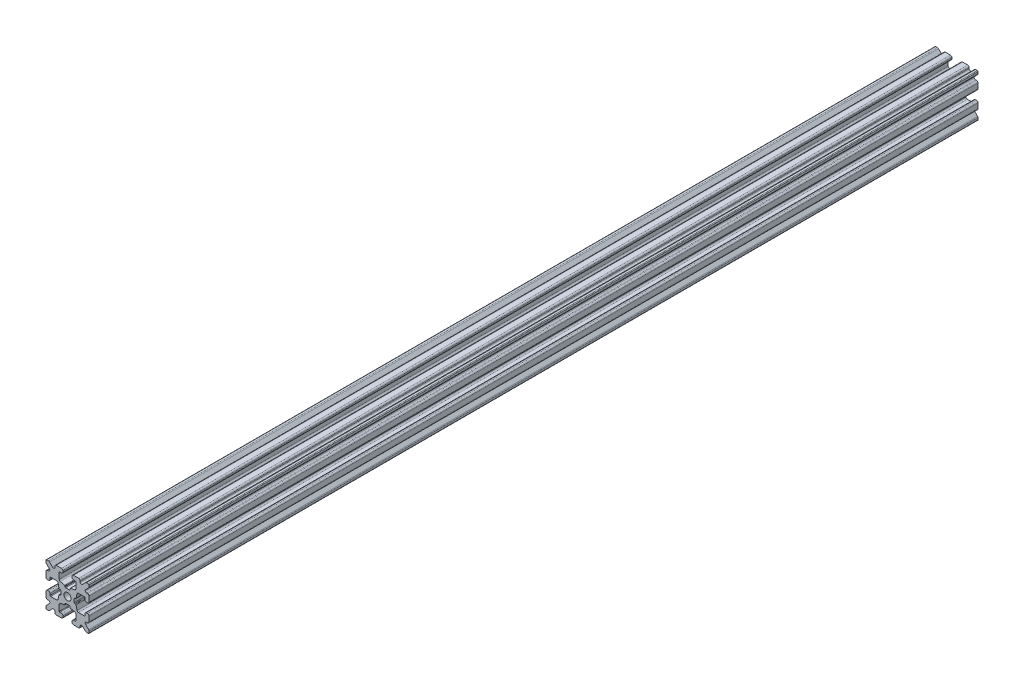
SolidWorks part; units mm, degrees
ref_plane "Alzado" through (0, 0, 0) normal (0, 0, 1) x (1, 0, 0)
ref_plane "Planta" through (0, 0, 0) normal (0, 1, 0) x (1, 0, 0)
ref_plane "Vista lateral" through (0, 0, 0) normal (1, 0, 0) x (0, 0, -1)
ref_plane "Plano1" through (0, 0, -150) normal (0, 0, -1) x (-1, 0, 0)
sketch "Croquis1" plane through (0, 0, -150) normal (0, 0, -1) x (-1, 0, 0)
  line L0 (-2.9, -5.9) -> (-2.9, -3.8003)
  line L1 (-2.5094, -3.3124) -> (-0.9818, -2.97)
  line L2 (-0.8255, -2.7749) -> (-0.8255, -2.5471)
  line L3 (-0.6255, -2.3471) -> (0.6255, -2.3471)
  line L4 (0.8255, -2.5471) -> (0.8255, -2.7749)
  line L5 (0.9818, -2.97) -> (2.5094, -3.3124)
  line L6 (2.9, -3.8003) -> (2.9, -5.9)
  line L7 (2.7, -6.1) -> (2.1, -6.1)
  line L8 (1.6, -6.6) -> (1.6, -7)
  line L9 (2.1, -7.5) -> (3.9, -7.5)
  line L10 (4.4, -7) -> (4.4, -6.6678)
  line L11 (5.2536, -6.3142) -> (6.2929, -7.3536)
  line L12 (6.6464, -7.5) -> (7.25, -7.5)
  line L13 (7.5, -7.25) -> (7.5, -6.6464)
  line L14 (7.3536, -6.2929) -> (6.3142, -5.2536)
  line L15 (6.6678, -4.4) -> (7, -4.4)
  line L16 (7.5, -3.9) -> (7.5, -2.1)
  line L17 (7, -1.6) -> (6.6, -1.6)
  line L18 (6.1, -2.1) -> (6.1, -2.7)
  line L19 (5.9, -2.9) -> (3.8003, -2.9)
  line L20 (3.3124, -2.5094) -> (2.97, -0.9818)
  line L21 (2.7749, -0.8255) -> (2.5471, -0.8255)
  line L22 (2.3471, -0.6255) -> (2.3471, 0.6255)
  line L23 (2.5471, 0.8255) -> (2.7749, 0.8255)
  line L24 (2.97, 0.9818) -> (3.3124, 2.5094)
  line L25 (3.8003, 2.9) -> (5.9, 2.9)
  line L26 (6.1, 2.7) -> (6.1, 2.1)
  line L27 (6.6, 1.6) -> (7, 1.6)
  line L28 (7.5, 2.1) -> (7.5, 3.9)
  line L29 (7, 4.4) -> (6.6678, 4.4)
  line L30 (6.3142, 5.2536) -> (7.3536, 6.2929)
  line L31 (7.5, 6.6464) -> (7.5, 7.25)
  line L32 (7.25, 7.5) -> (6.6464, 7.5)
  line L33 (6.2929, 7.3536) -> (5.2536, 6.3142)
  line L34 (4.4, 6.6678) -> (4.4, 7)
  line L35 (3.9, 7.5) -> (2.1, 7.5)
  line L36 (1.6, 7) -> (1.6, 6.6)
  line L37 (2.1, 6.1) -> (2.7, 6.1)
  line L38 (2.9, 5.9) -> (2.9, 3.8003)
  line L39 (2.5094, 3.3124) -> (0.9818, 2.97)
  line L40 (0.8255, 2.7749) -> (0.8255, 2.5471)
  line L41 (0.6255, 2.3471) -> (-0.6255, 2.3471)
  line L42 (-0.8255, 2.5471) -> (-0.8255, 2.7749)
  line L43 (-0.9818, 2.97) -> (-2.5094, 3.3124)
  line L44 (-2.9, 3.8003) -> (-2.9, 5.9)
  line L45 (-2.7, 6.1) -> (-2.1, 6.1)
  line L46 (-1.6, 6.6) -> (-1.6, 7)
  line L47 (-2.1, 7.5) -> (-3.9, 7.5)
  line L48 (-4.4, 7) -> (-4.4, 6.6678)
  line L49 (-5.2536, 6.3142) -> (-6.2929, 7.3536)
  line L50 (-6.6464, 7.5) -> (-7.25, 7.5)
  line L51 (-7.5, 7.25) -> (-7.5, 6.6464)
  line L52 (-7.3536, 6.2929) -> (-6.3142, 5.2536)
  line L53 (-6.6678, 4.4) -> (-7, 4.4)
  line L54 (-7.5, 3.9) -> (-7.5, 2.1)
  line L55 (-7, 1.6) -> (-6.6, 1.6)
  line L56 (-6.1, 2.1) -> (-6.1, 2.7)
  line L57 (-5.9, 2.9) -> (-3.8003, 2.9)
  line L58 (-3.3124, 2.5094) -> (-2.97, 0.9818)
  line L59 (-2.7749, 0.8255) -> (-2.5471, 0.8255)
  line L60 (-2.3471, 0.6255) -> (-2.3471, -0.6255)
  line L61 (-2.5471, -0.8255) -> (-2.7749, -0.8255)
  line L62 (-2.97, -0.9818) -> (-3.3124, -2.5094)
  line L63 (-3.8003, -2.9) -> (-5.9, -2.9)
  line L64 (-6.1, -2.7) -> (-6.1, -2.1)
  line L65 (-6.6, -1.6) -> (-7, -1.6)
  line L66 (-7.5, -2.1) -> (-7.5, -3.9)
  line L67 (-7, -4.4) -> (-6.6678, -4.4)
  line L68 (-6.3142, -5.2536) -> (-7.3536, -6.2929)
  line L69 (-7.5, -6.6464) -> (-7.5, -7.25)
  line L70 (-7.25, -7.5) -> (-6.6464, -7.5)
  line L71 (-6.2929, -7.3536) -> (-5.2536, -6.3142)
  line L72 (-4.4, -6.6678) -> (-4.4, -7)
  line L73 (-3.9, -7.5) -> (-2.1, -7.5)
  line L74 (-1.6, -7) -> (-1.6, -6.6)
  line L75 (-2.1, -6.1) -> (-2.7, -6.1)
  circle A0 centre (0, 0) radius 1.25
  arc A1 (-2.9, -3.8003) -> (-2.5094, -3.3124) centre (-2.4, -3.8003) cw
  arc A2 (-0.9818, -2.97) -> (-0.8255, -2.7749) centre (-1.0255, -2.7749) ccw
  arc A3 (-0.8255, -2.5471) -> (-0.6255, -2.3471) centre (-0.6255, -2.5471) cw
  arc A4 (0.6255, -2.3471) -> (0.8255, -2.5471) centre (0.6255, -2.5471) cw
  arc A5 (0.8255, -2.7749) -> (0.9818, -2.97) centre (1.0255, -2.7749) ccw
  arc A6 (2.5094, -3.3124) -> (2.9, -3.8003) centre (2.4, -3.8003) cw
  arc A7 (2.9, -5.9) -> (2.7, -6.1) centre (2.7, -5.9) cw
  arc A8 (2.1, -6.1) -> (1.6, -6.6) centre (2.1, -6.6) ccw
  arc A9 (1.6, -7) -> (2.1, -7.5) centre (2.1, -7) ccw
  arc A10 (3.9, -7.5) -> (4.4, -7) centre (3.9, -7) ccw
  arc A11 (4.4, -6.6678) -> (5.2536, -6.3142) centre (4.9, -6.6678) cw
  arc A12 (6.2929, -7.3536) -> (6.6464, -7.5) centre (6.6464, -7) ccw
  arc A13 (7.25, -7.5) -> (7.5, -7.25) centre (7.25, -7.25) ccw
  arc A14 (7.5, -6.6464) -> (7.3536, -6.2929) centre (7, -6.6464) ccw
  arc A15 (6.3142, -5.2536) -> (6.6678, -4.4) centre (6.6678, -4.9) cw
  arc A16 (7, -4.4) -> (7.5, -3.9) centre (7, -3.9) ccw
  arc A17 (7.5, -2.1) -> (7, -1.6) centre (7, -2.1) ccw
  arc A18 (6.6, -1.6) -> (6.1, -2.1) centre (6.6, -2.1) ccw
  arc A19 (6.1, -2.7) -> (5.9, -2.9) centre (5.9, -2.7) cw
  arc A20 (3.8003, -2.9) -> (3.3124, -2.5094) centre (3.8003, -2.4) cw
  arc A21 (2.97, -0.9818) -> (2.7749, -0.8255) centre (2.7749, -1.0255) ccw
  arc A22 (2.5471, -0.8255) -> (2.3471, -0.6255) centre (2.5471, -0.6255) cw
  arc A23 (2.3471, 0.6255) -> (2.5471, 0.8255) centre (2.5471, 0.6255) cw
  arc A24 (2.7749, 0.8255) -> (2.97, 0.9818) centre (2.7749, 1.0255) ccw
  arc A25 (3.3124, 2.5094) -> (3.8003, 2.9) centre (3.8003, 2.4) cw
  arc A26 (5.9, 2.9) -> (6.1, 2.7) centre (5.9, 2.7) cw
  arc A27 (6.1, 2.1) -> (6.6, 1.6) centre (6.6, 2.1) ccw
  arc A28 (7, 1.6) -> (7.5, 2.1) centre (7, 2.1) ccw
  arc A29 (7.5, 3.9) -> (7, 4.4) centre (7, 3.9) ccw
  arc A30 (6.6678, 4.4) -> (6.3142, 5.2536) centre (6.6678, 4.9) cw
  arc A31 (7.3536, 6.2929) -> (7.5, 6.6464) centre (7, 6.6464) ccw
  arc A32 (7.5, 7.25) -> (7.25, 7.5) centre (7.25, 7.25) ccw
  arc A33 (6.6464, 7.5) -> (6.2929, 7.3536) centre (6.6464, 7) ccw
  arc A34 (5.2536, 6.3142) -> (4.4, 6.6678) centre (4.9, 6.6678) cw
  arc A35 (4.4, 7) -> (3.9, 7.5) centre (3.9, 7) ccw
  arc A36 (2.1, 7.5) -> (1.6, 7) centre (2.1, 7) ccw
  arc A37 (1.6, 6.6) -> (2.1, 6.1) centre (2.1, 6.6) ccw
  arc A38 (2.7, 6.1) -> (2.9, 5.9) centre (2.7, 5.9) cw
  arc A39 (2.9, 3.8003) -> (2.5094, 3.3124) centre (2.4, 3.8003) cw
  arc A40 (0.9818, 2.97) -> (0.8255, 2.7749) centre (1.0255, 2.7749) ccw
  arc A41 (0.8255, 2.5471) -> (0.6255, 2.3471) centre (0.6255, 2.5471) cw
  arc A42 (-0.6255, 2.3471) -> (-0.8255, 2.5471) centre (-0.6255, 2.5471) cw
  arc A43 (-0.8255, 2.7749) -> (-0.9818, 2.97) centre (-1.0255, 2.7749) ccw
  arc A44 (-2.5094, 3.3124) -> (-2.9, 3.8003) centre (-2.4, 3.8003) cw
  arc A45 (-2.9, 5.9) -> (-2.7, 6.1) centre (-2.7, 5.9) cw
  arc A46 (-2.1, 6.1) -> (-1.6, 6.6) centre (-2.1, 6.6) ccw
  arc A47 (-1.6, 7) -> (-2.1, 7.5) centre (-2.1, 7) ccw
  arc A48 (-3.9, 7.5) -> (-4.4, 7) centre (-3.9, 7) ccw
  arc A49 (-4.4, 6.6678) -> (-5.2536, 6.3142) centre (-4.9, 6.6678) cw
  arc A50 (-6.2929, 7.3536) -> (-6.6464, 7.5) centre (-6.6464, 7) ccw
  arc A51 (-7.25, 7.5) -> (-7.5, 7.25) centre (-7.25, 7.25) ccw
  arc A52 (-7.5, 6.6464) -> (-7.3536, 6.2929) centre (-7, 6.6464) ccw
  arc A53 (-6.3142, 5.2536) -> (-6.6678, 4.4) centre (-6.6678, 4.9) cw
  arc A54 (-7, 4.4) -> (-7.5, 3.9) centre (-7, 3.9) ccw
  arc A55 (-7.5, 2.1) -> (-7, 1.6) centre (-7, 2.1) ccw
  arc A56 (-6.6, 1.6) -> (-6.1, 2.1) centre (-6.6, 2.1) ccw
  arc A57 (-6.1, 2.7) -> (-5.9, 2.9) centre (-5.9, 2.7) cw
  arc A58 (-3.8003, 2.9) -> (-3.3124, 2.5094) centre (-3.8003, 2.4) cw
  arc A59 (-2.97, 0.9818) -> (-2.7749, 0.8255) centre (-2.7749, 1.0255) ccw
  arc A60 (-2.5471, 0.8255) -> (-2.3471, 0.6255) centre (-2.5471, 0.6255) cw
  arc A61 (-2.3471, -0.6255) -> (-2.5471, -0.8255) centre (-2.5471, -0.6255) cw
  arc A62 (-2.7749, -0.8255) -> (-2.97, -0.9818) centre (-2.7749, -1.0255) ccw
  arc A63 (-3.3124, -2.5094) -> (-3.8003, -2.9) centre (-3.8003, -2.4) cw
  arc A64 (-5.9, -2.9) -> (-6.1, -2.7) centre (-5.9, -2.7) cw
  arc A65 (-6.1, -2.1) -> (-6.6, -1.6) centre (-6.6, -2.1) ccw
  arc A66 (-7, -1.6) -> (-7.5, -2.1) centre (-7, -2.1) ccw
  arc A67 (-7.5, -3.9) -> (-7, -4.4) centre (-7, -3.9) ccw
  arc A68 (-6.6678, -4.4) -> (-6.3142, -5.2536) centre (-6.6678, -4.9) cw
  arc A69 (-7.3536, -6.2929) -> (-7.5, -6.6464) centre (-7, -6.6464) ccw
  arc A70 (-7.5, -7.25) -> (-7.25, -7.5) centre (-7.25, -7.25) ccw
  arc A71 (-6.6464, -7.5) -> (-6.2929, -7.3536) centre (-6.6464, -7) ccw
  arc A72 (-5.2536, -6.3142) -> (-4.4, -6.6678) centre (-4.9, -6.6678) cw
  arc A73 (-4.4, -7) -> (-3.9, -7.5) centre (-3.9, -7) ccw
  arc A74 (-2.1, -7.5) -> (-1.6, -7) centre (-2.1, -7) ccw
  arc A75 (-1.6, -6.6) -> (-2.1, -6.1) centre (-2.1, -6.6) ccw
  arc A76 (-2.7, -6.1) -> (-2.9, -5.9) centre (-2.7, -5.9) cw
extrude "Saliente-Extruir1" add sketch "Croquis1" against normal blind 300
sketch "Croquis2" plane through (0, 0, 150) normal (0, 0, 1) x (1, 0, 0)
  line L76 (2.7, -6.1) -> (2.1, -6.1)
  line L77 (1.6, -6.6) -> (1.6, -7)
  line L78 (2.1, -7.5) -> (3.9, -7.5)
  line L79 (4.4, -7) -> (4.4, -6.6678)
  line L80 (5.2536, -6.3142) -> (6.2929, -7.3536)
  line L81 (6.6464, -7.5) -> (7.25, -7.5)
  line L82 (7.5, -7.25) -> (7.5, -6.6464)
  line L83 (7.3536, -6.2929) -> (6.3142, -5.2536)
  line L84 (6.6678, -4.4) -> (7, -4.4)
  line L85 (7.5, -3.9) -> (7.5, -2.1)
  line L86 (7, -1.6) -> (6.6, -1.6)
  line L87 (6.1, -2.1) -> (6.1, -2.7)
  line L88 (5.9, -2.9) -> (3.8003, -2.9)
  line L89 (3.3124, -2.5094) -> (2.97, -0.9818)
  line L90 (2.7749, -0.8255) -> (2.5471, -0.8255)
  line L91 (2.3471, -0.6255) -> (2.3471, 0.6255)
  line L92 (2.5471, 0.8255) -> (2.7749, 0.8255)
  line L93 (2.97, 0.9818) -> (3.3124, 2.5094)
  line L94 (3.8003, 2.9) -> (5.9, 2.9)
  line L95 (6.1, 2.7) -> (6.1, 2.1)
  line L96 (6.6, 1.6) -> (7, 1.6)
  line L97 (7.5, 2.1) -> (7.5, 3.9)
  line L98 (7, 4.4) -> (6.6678, 4.4)
  line L99 (6.3142, 5.2536) -> (7.3536, 6.2929)
  line L100 (7.5, 6.6464) -> (7.5, 7.25)
  line L101 (7.25, 7.5) -> (6.6464, 7.5)
  line L102 (6.2929, 7.3536) -> (5.2536, 6.3142)
  line L103 (4.4, 6.6678) -> (4.4, 7)
  line L104 (3.9, 7.5) -> (2.1, 7.5)
  line L105 (1.6, 7) -> (1.6, 6.6)
  line L106 (2.1, 6.1) -> (2.7, 6.1)
  line L107 (2.9, 5.9) -> (2.9, 3.8003)
  line L108 (2.5094, 3.3124) -> (0.9818, 2.97)
  line L109 (0.8255, 2.7749) -> (0.8255, 2.5471)
  line L110 (0.6255, 2.3471) -> (-0.6255, 2.3471)
  line L111 (-0.8255, 2.5471) -> (-0.8255, 2.7749)
  line L112 (-0.9818, 2.97) -> (-2.5094, 3.3124)
  line L113 (-2.9, 3.8003) -> (-2.9, 5.9)
  line L114 (-2.7, 6.1) -> (-2.1, 6.1)
  line L115 (-1.6, 6.6) -> (-1.6, 7)
  line L116 (-2.1, 7.5) -> (-3.9, 7.5)
  line L117 (-4.4, 7) -> (-4.4, 6.6678)
  line L118 (-5.2536, 6.3142) -> (-6.2929, 7.3536)
  line L119 (-6.6464, 7.5) -> (-7.25, 7.5)
  line L120 (-7.5, 7.25) -> (-7.5, 6.6464)
  line L121 (-7.3536, 6.2929) -> (-6.3142, 5.2536)
  line L122 (-6.6678, 4.4) -> (-7, 4.4)
  line L123 (-7.5, 3.9) -> (-7.5, 2.1)
  line L124 (-7, 1.6) -> (-6.6, 1.6)
  line L125 (-6.1, 2.1) -> (-6.1, 2.7)
  line L126 (-5.9, 2.9) -> (-3.8003, 2.9)
  line L127 (-3.3124, 2.5094) -> (-2.97, 0.9818)
  line L128 (-2.7749, 0.8255) -> (-2.5471, 0.8255)
  line L129 (-2.3471, 0.6255) -> (-2.3471, -0.6255)
  line L130 (-2.5471, -0.8255) -> (-2.7749, -0.8255)
  line L131 (-2.97, -0.9818) -> (-3.3124, -2.5094)
  line L132 (-3.8003, -2.9) -> (-5.9, -2.9)
  line L133 (-6.1, -2.7) -> (-6.1, -2.1)
  line L134 (-6.6, -1.6) -> (-7, -1.6)
  line L135 (-7.5, -2.1) -> (-7.5, -3.9)
  line L136 (-7, -4.4) -> (-6.6678, -4.4)
  line L137 (-6.3142, -5.2536) -> (-7.3536, -6.2929)
  line L138 (-7.5, -6.6464) -> (-7.5, -7.25)
  line L139 (-7.25, -7.5) -> (-6.6464, -7.5)
  line L140 (-6.2929, -7.3536) -> (-5.2536, -6.3142)
  line L141 (-4.4, -6.6678) -> (-4.4, -7)
  line L142 (-3.9, -7.5) -> (-2.1, -7.5)
  line L143 (-1.6, -7) -> (-1.6, -6.6)
  line L144 (-2.1, -6.1) -> (-2.7, -6.1)
  line L145 (-2.9, -5.9) -> (-2.9, -3.8003)
  line L146 (-2.5094, -3.3124) -> (-0.9818, -2.97)
  line L147 (-0.8255, -2.7749) -> (-0.8255, -2.5471)
  line L148 (-0.6255, -2.3471) -> (0.6255, -2.3471)
  line L149 (0.8255, -2.5471) -> (0.8255, -2.7749)
  line L150 (0.9818, -2.97) -> (2.5094, -3.3124)
  line L151 (2.9, -3.8003) -> (2.9, -5.9)
  line L152 (2.7, -6.1) -> (2.1, -6.1)
  line L153 (1.6, -6.6) -> (1.6, -7)
  line L154 (2.1, -7.5) -> (3.9, -7.5)
  line L155 (4.4, -7) -> (4.4, -6.6678)
  line L156 (5.2536, -6.3142) -> (6.2929, -7.3536)
  line L157 (6.6464, -7.5) -> (7.25, -7.5)
  line L158 (7.5, -7.25) -> (7.5, -6.6464)
  line L159 (7.3536, -6.2929) -> (6.3142, -5.2536)
  line L160 (6.6678, -4.4) -> (7, -4.4)
  line L161 (7.5, -3.9) -> (7.5, -2.1)
  line L162 (7, -1.6) -> (6.6, -1.6)
  line L163 (6.1, -2.1) -> (6.1, -2.7)
  line L164 (5.9, -2.9) -> (3.8003, -2.9)
  line L165 (3.3124, -2.5094) -> (2.97, -0.9818)
  line L166 (2.7749, -0.8255) -> (2.5471, -0.8255)
  line L167 (2.3471, -0.6255) -> (2.3471, 0.6255)
  line L168 (2.5471, 0.8255) -> (2.7749, 0.8255)
  line L169 (2.97, 0.9818) -> (3.3124, 2.5094)
  line L170 (3.8003, 2.9) -> (5.9, 2.9)
  line L171 (6.1, 2.7) -> (6.1, 2.1)
  line L172 (6.6, 1.6) -> (7, 1.6)
  line L173 (7.5, 2.1) -> (7.5, 3.9)
  line L174 (7, 4.4) -> (6.6678, 4.4)
  line L175 (6.3142, 5.2536) -> (7.3536, 6.2929)
  line L176 (7.5, 6.6464) -> (7.5, 7.25)
  line L177 (7.25, 7.5) -> (6.6464, 7.5)
  line L178 (6.2929, 7.3536) -> (5.2536, 6.3142)
  line L179 (4.4, 6.6678) -> (4.4, 7)
  line L180 (3.9, 7.5) -> (2.1, 7.5)
  line L181 (1.6, 7) -> (1.6, 6.6)
  line L182 (2.1, 6.1) -> (2.7, 6.1)
  line L183 (2.9, 5.9) -> (2.9, 3.8003)
  line L184 (2.5094, 3.3124) -> (0.9818, 2.97)
  line L185 (0.8255, 2.7749) -> (0.8255, 2.5471)
  line L186 (0.6255, 2.3471) -> (-0.6255, 2.3471)
  line L187 (-0.8255, 2.5471) -> (-0.8255, 2.7749)
  line L188 (-0.9818, 2.97) -> (-2.5094, 3.3124)
  line L189 (-2.9, 3.8003) -> (-2.9, 5.9)
  line L190 (-2.7, 6.1) -> (-2.1, 6.1)
  line L191 (-1.6, 6.6) -> (-1.6, 7)
  line L192 (-2.1, 7.5) -> (-3.9, 7.5)
  line L193 (-4.4, 7) -> (-4.4, 6.6678)
  line L194 (-5.2536, 6.3142) -> (-6.2929, 7.3536)
  line L195 (-6.6464, 7.5) -> (-7.25, 7.5)
  line L196 (-7.5, 7.25) -> (-7.5, 6.6464)
  line L197 (-7.3536, 6.2929) -> (-6.3142, 5.2536)
  line L198 (-6.6678, 4.4) -> (-7, 4.4)
  line L199 (-7.5, 3.9) -> (-7.5, 2.1)
  line L200 (-7, 1.6) -> (-6.6, 1.6)
  line L201 (-6.1, 2.1) -> (-6.1, 2.7)
  line L202 (-5.9, 2.9) -> (-3.8003, 2.9)
  line L203 (-3.3124, 2.5094) -> (-2.97, 0.9818)
  line L204 (-2.7749, 0.8255) -> (-2.5471, 0.8255)
  line L205 (-2.3471, 0.6255) -> (-2.3471, -0.6255)
  line L206 (-2.5471, -0.8255) -> (-2.7749, -0.8255)
  line L207 (-2.97, -0.9818) -> (-3.3124, -2.5094)
  line L208 (-3.8003, -2.9) -> (-5.9, -2.9)
  line L209 (-6.1, -2.7) -> (-6.1, -2.1)
  line L210 (-6.6, -1.6) -> (-7, -1.6)
  line L211 (-7.5, -2.1) -> (-7.5, -3.9)
  line L212 (-7, -4.4) -> (-6.6678, -4.4)
  line L213 (-6.3142, -5.2536) -> (-7.3536, -6.2929)
  line L214 (-7.5, -6.6464) -> (-7.5, -7.25)
  line L215 (-7.25, -7.5) -> (-6.6464, -7.5)
  line L216 (-6.2929, -7.3536) -> (-5.2536, -6.3142)
  line L217 (-4.4, -6.6678) -> (-4.4, -7)
  line L218 (-3.9, -7.5) -> (-2.1, -7.5)
  line L219 (-1.6, -7) -> (-1.6, -6.6)
  line L220 (-2.1, -6.1) -> (-2.7, -6.1)
  line L221 (-2.9, -5.9) -> (-2.9, -3.8003)
  line L222 (-2.5094, -3.3124) -> (-0.9818, -2.97)
  line L223 (-0.8255, -2.7749) -> (-0.8255, -2.5471)
  line L224 (-0.6255, -2.3471) -> (0.6255, -2.3471)
  line L225 (0.8255, -2.5471) -> (0.8255, -2.7749)
  line L226 (0.9818, -2.97) -> (2.5094, -3.3124)
  line L227 (2.9, -3.8003) -> (2.9, -5.9)
  circle A0 centre (0, 0) radius 1.25 construction
  circle A1 centre (0, 0) radius 1.25
  arc A76 (2.7, -6.1) -> (2.9, -5.9) centre (2.7, -5.9) ccw
  arc A77 (2.1, -6.1) -> (1.6, -6.6) centre (2.1, -6.6) ccw
  arc A78 (1.6, -7) -> (2.1, -7.5) centre (2.1, -7) ccw
  arc A79 (3.9, -7.5) -> (4.4, -7) centre (3.9, -7) ccw
  arc A80 (5.2536, -6.3142) -> (4.4, -6.6678) centre (4.9, -6.6678) ccw
  arc A81 (6.2929, -7.3536) -> (6.6464, -7.5) centre (6.6464, -7) ccw
  arc A82 (7.25, -7.5) -> (7.5, -7.25) centre (7.25, -7.25) ccw
  arc A83 (7.5, -6.6464) -> (7.3536, -6.2929) centre (7, -6.6464) ccw
  arc A84 (6.6678, -4.4) -> (6.3142, -5.2536) centre (6.6678, -4.9) ccw
  arc A85 (7, -4.4) -> (7.5, -3.9) centre (7, -3.9) ccw
  arc A86 (7.5, -2.1) -> (7, -1.6) centre (7, -2.1) ccw
  arc A87 (6.6, -1.6) -> (6.1, -2.1) centre (6.6, -2.1) ccw
  arc A88 (5.9, -2.9) -> (6.1, -2.7) centre (5.9, -2.7) ccw
  arc A89 (3.3124, -2.5094) -> (3.8003, -2.9) centre (3.8003, -2.4) ccw
  arc A90 (2.97, -0.9818) -> (2.7749, -0.8255) centre (2.7749, -1.0255) ccw
  arc A91 (2.3471, -0.6255) -> (2.5471, -0.8255) centre (2.5471, -0.6255) ccw
  arc A92 (2.5471, 0.8255) -> (2.3471, 0.6255) centre (2.5471, 0.6255) ccw
  arc A93 (2.7749, 0.8255) -> (2.97, 0.9818) centre (2.7749, 1.0255) ccw
  arc A94 (3.8003, 2.9) -> (3.3124, 2.5094) centre (3.8003, 2.4) ccw
  arc A95 (6.1, 2.7) -> (5.9, 2.9) centre (5.9, 2.7) ccw
  arc A96 (6.1, 2.1) -> (6.6, 1.6) centre (6.6, 2.1) ccw
  arc A97 (7, 1.6) -> (7.5, 2.1) centre (7, 2.1) ccw
  arc A98 (7.5, 3.9) -> (7, 4.4) centre (7, 3.9) ccw
  arc A99 (6.3142, 5.2536) -> (6.6678, 4.4) centre (6.6678, 4.9) ccw
  arc A100 (7.3536, 6.2929) -> (7.5, 6.6464) centre (7, 6.6464) ccw
  arc A101 (7.5, 7.25) -> (7.25, 7.5) centre (7.25, 7.25) ccw
  arc A102 (6.6464, 7.5) -> (6.2929, 7.3536) centre (6.6464, 7) ccw
  arc A103 (4.4, 6.6678) -> (5.2536, 6.3142) centre (4.9, 6.6678) ccw
  arc A104 (4.4, 7) -> (3.9, 7.5) centre (3.9, 7) ccw
  arc A105 (2.1, 7.5) -> (1.6, 7) centre (2.1, 7) ccw
  arc A106 (1.6, 6.6) -> (2.1, 6.1) centre (2.1, 6.6) ccw
  arc A107 (2.9, 5.9) -> (2.7, 6.1) centre (2.7, 5.9) ccw
  arc A108 (2.5094, 3.3124) -> (2.9, 3.8003) centre (2.4, 3.8003) ccw
  arc A109 (0.9818, 2.97) -> (0.8255, 2.7749) centre (1.0255, 2.7749) ccw
  arc A110 (0.6255, 2.3471) -> (0.8255, 2.5471) centre (0.6255, 2.5471) ccw
  arc A111 (-0.8255, 2.5471) -> (-0.6255, 2.3471) centre (-0.6255, 2.5471) ccw
  arc A112 (-0.8255, 2.7749) -> (-0.9818, 2.97) centre (-1.0255, 2.7749) ccw
  arc A113 (-2.9, 3.8003) -> (-2.5094, 3.3124) centre (-2.4, 3.8003) ccw
  arc A114 (-2.7, 6.1) -> (-2.9, 5.9) centre (-2.7, 5.9) ccw
  arc A115 (-2.1, 6.1) -> (-1.6, 6.6) centre (-2.1, 6.6) ccw
  arc A116 (-1.6, 7) -> (-2.1, 7.5) centre (-2.1, 7) ccw
  arc A117 (-3.9, 7.5) -> (-4.4, 7) centre (-3.9, 7) ccw
  arc A118 (-5.2536, 6.3142) -> (-4.4, 6.6678) centre (-4.9, 6.6678) ccw
  arc A119 (-6.2929, 7.3536) -> (-6.6464, 7.5) centre (-6.6464, 7) ccw
  arc A120 (-7.25, 7.5) -> (-7.5, 7.25) centre (-7.25, 7.25) ccw
  arc A121 (-7.5, 6.6464) -> (-7.3536, 6.2929) centre (-7, 6.6464) ccw
  arc A122 (-6.6678, 4.4) -> (-6.3142, 5.2536) centre (-6.6678, 4.9) ccw
  arc A123 (-7, 4.4) -> (-7.5, 3.9) centre (-7, 3.9) ccw
  arc A124 (-7.5, 2.1) -> (-7, 1.6) centre (-7, 2.1) ccw
  arc A125 (-6.6, 1.6) -> (-6.1, 2.1) centre (-6.6, 2.1) ccw
  arc A126 (-5.9, 2.9) -> (-6.1, 2.7) centre (-5.9, 2.7) ccw
  arc A127 (-3.3124, 2.5094) -> (-3.8003, 2.9) centre (-3.8003, 2.4) ccw
  arc A128 (-2.97, 0.9818) -> (-2.7749, 0.8255) centre (-2.7749, 1.0255) ccw
  arc A129 (-2.3471, 0.6255) -> (-2.5471, 0.8255) centre (-2.5471, 0.6255) ccw
  arc A130 (-2.5471, -0.8255) -> (-2.3471, -0.6255) centre (-2.5471, -0.6255) ccw
  arc A131 (-2.7749, -0.8255) -> (-2.97, -0.9818) centre (-2.7749, -1.0255) ccw
  arc A132 (-3.8003, -2.9) -> (-3.3124, -2.5094) centre (-3.8003, -2.4) ccw
  arc A133 (-6.1, -2.7) -> (-5.9, -2.9) centre (-5.9, -2.7) ccw
  arc A134 (-6.1, -2.1) -> (-6.6, -1.6) centre (-6.6, -2.1) ccw
  arc A135 (-7, -1.6) -> (-7.5, -2.1) centre (-7, -2.1) ccw
  arc A136 (-7.5, -3.9) -> (-7, -4.4) centre (-7, -3.9) ccw
  arc A137 (-6.3142, -5.2536) -> (-6.6678, -4.4) centre (-6.6678, -4.9) ccw
  arc A138 (-7.3536, -6.2929) -> (-7.5, -6.6464) centre (-7, -6.6464) ccw
  arc A139 (-7.5, -7.25) -> (-7.25, -7.5) centre (-7.25, -7.25) ccw
  arc A140 (-6.6464, -7.5) -> (-6.2929, -7.3536) centre (-6.6464, -7) ccw
  arc A141 (-4.4, -6.6678) -> (-5.2536, -6.3142) centre (-4.9, -6.6678) ccw
  arc A142 (-4.4, -7) -> (-3.9, -7.5) centre (-3.9, -7) ccw
  arc A143 (-2.1, -7.5) -> (-1.6, -7) centre (-2.1, -7) ccw
  arc A144 (-1.6, -6.6) -> (-2.1, -6.1) centre (-2.1, -6.6) ccw
  arc A145 (-2.9, -5.9) -> (-2.7, -6.1) centre (-2.7, -5.9) ccw
  arc A146 (-2.5094, -3.3124) -> (-2.9, -3.8003) centre (-2.4, -3.8003) ccw
  arc A147 (-0.9818, -2.97) -> (-0.8255, -2.7749) centre (-1.0255, -2.7749) ccw
  arc A148 (-0.6255, -2.3471) -> (-0.8255, -2.5471) centre (-0.6255, -2.5471) ccw
  arc A149 (0.8255, -2.5471) -> (0.6255, -2.3471) centre (0.6255, -2.5471) ccw
  arc A150 (0.8255, -2.7749) -> (0.9818, -2.97) centre (1.0255, -2.7749) ccw
  arc A151 (2.9, -3.8003) -> (2.5094, -3.3124) centre (2.4, -3.8003) ccw
  arc A152 (2.7, -6.1) -> (2.9, -5.9) centre (2.7, -5.9) ccw
  arc A153 (2.1, -6.1) -> (1.6, -6.6) centre (2.1, -6.6) ccw
  arc A154 (1.6, -7) -> (2.1, -7.5) centre (2.1, -7) ccw
  arc A155 (3.9, -7.5) -> (4.4, -7) centre (3.9, -7) ccw
  arc A156 (5.2536, -6.3142) -> (4.4, -6.6678) centre (4.9, -6.6678) ccw
  arc A157 (6.2929, -7.3536) -> (6.6464, -7.5) centre (6.6464, -7) ccw
  arc A158 (7.25, -7.5) -> (7.5, -7.25) centre (7.25, -7.25) ccw
  arc A159 (7.5, -6.6464) -> (7.3536, -6.2929) centre (7, -6.6464) ccw
  arc A160 (6.6678, -4.4) -> (6.3142, -5.2536) centre (6.6678, -4.9) ccw
  arc A161 (7, -4.4) -> (7.5, -3.9) centre (7, -3.9) ccw
  arc A162 (7.5, -2.1) -> (7, -1.6) centre (7, -2.1) ccw
  arc A163 (6.6, -1.6) -> (6.1, -2.1) centre (6.6, -2.1) ccw
  arc A164 (5.9, -2.9) -> (6.1, -2.7) centre (5.9, -2.7) ccw
  arc A165 (3.3124, -2.5094) -> (3.8003, -2.9) centre (3.8003, -2.4) ccw
  arc A166 (2.97, -0.9818) -> (2.7749, -0.8255) centre (2.7749, -1.0255) ccw
  arc A167 (2.3471, -0.6255) -> (2.5471, -0.8255) centre (2.5471, -0.6255) ccw
  arc A168 (2.5471, 0.8255) -> (2.3471, 0.6255) centre (2.5471, 0.6255) ccw
  arc A169 (2.7749, 0.8255) -> (2.97, 0.9818) centre (2.7749, 1.0255) ccw
  arc A170 (3.8003, 2.9) -> (3.3124, 2.5094) centre (3.8003, 2.4) ccw
  arc A171 (6.1, 2.7) -> (5.9, 2.9) centre (5.9, 2.7) ccw
  arc A172 (6.1, 2.1) -> (6.6, 1.6) centre (6.6, 2.1) ccw
  arc A173 (7, 1.6) -> (7.5, 2.1) centre (7, 2.1) ccw
  arc A174 (7.5, 3.9) -> (7, 4.4) centre (7, 3.9) ccw
  arc A175 (6.3142, 5.2536) -> (6.6678, 4.4) centre (6.6678, 4.9) ccw
  arc A176 (7.3536, 6.2929) -> (7.5, 6.6464) centre (7, 6.6464) ccw
  arc A177 (7.5, 7.25) -> (7.25, 7.5) centre (7.25, 7.25) ccw
  arc A178 (6.6464, 7.5) -> (6.2929, 7.3536) centre (6.6464, 7) ccw
  arc A179 (4.4, 6.6678) -> (5.2536, 6.3142) centre (4.9, 6.6678) ccw
  arc A180 (4.4, 7) -> (3.9, 7.5) centre (3.9, 7) ccw
  arc A181 (2.1, 7.5) -> (1.6, 7) centre (2.1, 7) ccw
  arc A182 (1.6, 6.6) -> (2.1, 6.1) centre (2.1, 6.6) ccw
  arc A183 (2.9, 5.9) -> (2.7, 6.1) centre (2.7, 5.9) ccw
  arc A184 (2.5094, 3.3124) -> (2.9, 3.8003) centre (2.4, 3.8003) ccw
  arc A185 (0.9818, 2.97) -> (0.8255, 2.7749) centre (1.0255, 2.7749) ccw
  arc A186 (0.6255, 2.3471) -> (0.8255, 2.5471) centre (0.6255, 2.5471) ccw
  arc A187 (-0.8255, 2.5471) -> (-0.6255, 2.3471) centre (-0.6255, 2.5471) ccw
  arc A188 (-0.8255, 2.7749) -> (-0.9818, 2.97) centre (-1.0255, 2.7749) ccw
  arc A189 (-2.9, 3.8003) -> (-2.5094, 3.3124) centre (-2.4, 3.8003) ccw
  arc A190 (-2.7, 6.1) -> (-2.9, 5.9) centre (-2.7, 5.9) ccw
  arc A191 (-2.1, 6.1) -> (-1.6, 6.6) centre (-2.1, 6.6) ccw
  arc A192 (-1.6, 7) -> (-2.1, 7.5) centre (-2.1, 7) ccw
  arc A193 (-3.9, 7.5) -> (-4.4, 7) centre (-3.9, 7) ccw
  arc A194 (-5.2536, 6.3142) -> (-4.4, 6.6678) centre (-4.9, 6.6678) ccw
  arc A195 (-6.2929, 7.3536) -> (-6.6464, 7.5) centre (-6.6464, 7) ccw
  arc A196 (-7.25, 7.5) -> (-7.5, 7.25) centre (-7.25, 7.25) ccw
  arc A197 (-7.5, 6.6464) -> (-7.3536, 6.2929) centre (-7, 6.6464) ccw
  arc A198 (-6.6678, 4.4) -> (-6.3142, 5.2536) centre (-6.6678, 4.9) ccw
  arc A199 (-7, 4.4) -> (-7.5, 3.9) centre (-7, 3.9) ccw
  arc A200 (-7.5, 2.1) -> (-7, 1.6) centre (-7, 2.1) ccw
  arc A201 (-6.6, 1.6) -> (-6.1, 2.1) centre (-6.6, 2.1) ccw
  arc A202 (-5.9, 2.9) -> (-6.1, 2.7) centre (-5.9, 2.7) ccw
  arc A203 (-3.3124, 2.5094) -> (-3.8003, 2.9) centre (-3.8003, 2.4) ccw
  arc A204 (-2.97, 0.9818) -> (-2.7749, 0.8255) centre (-2.7749, 1.0255) ccw
  arc A205 (-2.3471, 0.6255) -> (-2.5471, 0.8255) centre (-2.5471, 0.6255) ccw
  arc A206 (-2.5471, -0.8255) -> (-2.3471, -0.6255) centre (-2.5471, -0.6255) ccw
  arc A207 (-2.7749, -0.8255) -> (-2.97, -0.9818) centre (-2.7749, -1.0255) ccw
  arc A208 (-3.8003, -2.9) -> (-3.3124, -2.5094) centre (-3.8003, -2.4) ccw
  arc A209 (-6.1, -2.7) -> (-5.9, -2.9) centre (-5.9, -2.7) ccw
  arc A210 (-6.1, -2.1) -> (-6.6, -1.6) centre (-6.6, -2.1) ccw
  arc A211 (-7, -1.6) -> (-7.5, -2.1) centre (-7, -2.1) ccw
  arc A212 (-7.5, -3.9) -> (-7, -4.4) centre (-7, -3.9) ccw
  arc A213 (-6.3142, -5.2536) -> (-6.6678, -4.4) centre (-6.6678, -4.9) ccw
  arc A214 (-7.3536, -6.2929) -> (-7.5, -6.6464) centre (-7, -6.6464) ccw
  arc A215 (-7.5, -7.25) -> (-7.25, -7.5) centre (-7.25, -7.25) ccw
  arc A216 (-6.6464, -7.5) -> (-6.2929, -7.3536) centre (-6.6464, -7) ccw
  arc A217 (-4.4, -6.6678) -> (-5.2536, -6.3142) centre (-4.9, -6.6678) ccw
  arc A218 (-4.4, -7) -> (-3.9, -7.5) centre (-3.9, -7) ccw
  arc A219 (-2.1, -7.5) -> (-1.6, -7) centre (-2.1, -7) ccw
  arc A220 (-1.6, -6.6) -> (-2.1, -6.1) centre (-2.1, -6.6) ccw
  arc A221 (-2.9, -5.9) -> (-2.7, -6.1) centre (-2.7, -5.9) ccw
  arc A222 (-2.5094, -3.3124) -> (-2.9, -3.8003) centre (-2.4, -3.8003) ccw
  arc A223 (-0.9818, -2.97) -> (-0.8255, -2.7749) centre (-1.0255, -2.7749) ccw
  arc A224 (-0.6255, -2.3471) -> (-0.8255, -2.5471) centre (-0.6255, -2.5471) ccw
  arc A225 (0.8255, -2.5471) -> (0.6255, -2.3471) centre (0.6255, -2.5471) ccw
  arc A226 (0.8255, -2.7749) -> (0.9818, -2.97) centre (1.0255, -2.7749) ccw
  arc A227 (2.9, -3.8003) -> (2.5094, -3.3124) centre (2.4, -3.8003) ccw
  dimension "D1" = 0
extrude "Saliente-Extruir2" add sketch "Croquis2" along normal blind 40
sketch "Croquis3" plane through (0, 0, 190) normal (0, 0, 1) x (1, 0, 0)
  line L1 (-15.8155, 9.125) -> (18.2409, 9.125)
  line L2 (-15.8155, 9.125) -> (-15.8155, -10.4762)
  line L3 (-15.8155, -10.4762) -> (18.2409, -10.4762)
  line L4 (18.2409, 9.125) -> (18.2409, -10.4762)
extrude "Cortar-Extruir1" cut sketch "Croquis3" against normal blind 30
